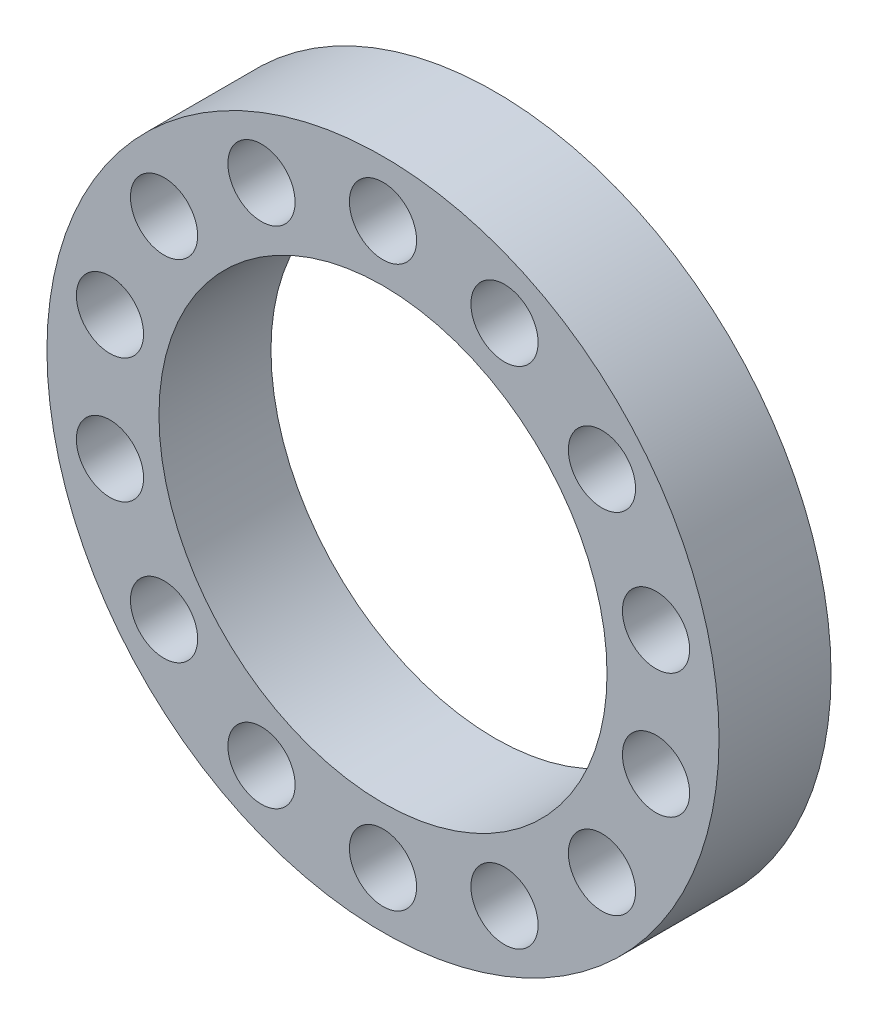
SolidWorks part; units mm, degrees
ref_plane "Plan de face" through (0, 0, 0) normal (0, 0, 1) x (1, 0, 0)
ref_plane "Plan de dessus" through (0, 0, 0) normal (0, 1, 0) x (1, 0, 0)
ref_plane "Plan de droite" through (0, 0, 0) normal (1, 0, 0) x (0, 0, -1)
sketch "Esquisse1" plane through (0, 0, 0) normal (0, 0, 1) x (1, 0, 0)
  circle A0 centre (0, 0) radius 100
  circle A1 centre (0, 0) radius 150
  dimension "D1" = 300
  dimension "D2" = 200
extrude "Boss.-Extru.1" add sketch "Esquisse1" along normal blind 50
sketch "Esquisse2" plane through (0, 0, 50) normal (0, 0, 1) x (1, 0, 0)
  line L0 (0, 100) -> (0, 150) construction
  circle A0 centre (0, 0) radius 100 construction
  circle A1 centre (0, 0) radius 150 construction
  circle A2 centre (0, 125) radius 15
  circle A3 centre (54.2355, 112.6211) radius 15
  circle A4 centre (97.7289, 77.9362) radius 15
  circle A5 centre (121.866, 27.8151) radius 15
  circle A6 centre (121.866, -27.8151) radius 15
  circle A7 centre (97.7289, -77.9362) radius 15
  circle A8 centre (54.2355, -112.6211) radius 15
  circle A9 centre (0, -125) radius 15
  circle A10 centre (-54.2355, -112.6211) radius 15
  circle A11 centre (-97.7289, -77.9362) radius 15
  circle A12 centre (-121.866, -27.8151) radius 15
  circle A13 centre (-121.866, 27.8151) radius 15
  circle A14 centre (-97.7289, 77.9362) radius 15
  circle A15 centre (-54.2355, 112.6211) radius 15
  point P37 (0, 0)
  dimension "D1" = 30
  dimension "D2" = 14
extrude "Enlèv. mat.-Extru.1" cut sketch "Esquisse2" against normal blind 40
sketch "Esquisse3" plane through (0, 0, 10) normal (0, 0, 1) x (1, 0, 0)
  circle A0 centre (0, 125) radius 6
  circle A1 centre (54.2355, 112.6211) radius 6
  circle A2 centre (97.7289, 77.9362) radius 6
  circle A3 centre (121.866, 27.8151) radius 6
  circle A4 centre (121.866, -27.8151) radius 6
  circle A5 centre (97.7289, -77.9362) radius 6
  circle A6 centre (54.2355, -112.6211) radius 6
  circle A7 centre (0, -125) radius 6
  circle A8 centre (-54.2355, -112.6211) radius 6
  circle A9 centre (-97.7289, -77.9362) radius 6
  circle A10 centre (-121.866, -27.8151) radius 6
  circle A11 centre (-121.866, 27.8151) radius 6
  circle A12 centre (-97.7289, 77.9362) radius 6
  circle A13 centre (-54.2355, 112.6211) radius 6
  point P31 (0, 0)
  dimension "D1" = 12
  dimension "D2" = 14
extrude "Enlèv. mat.-Extru.2" cut sketch "Esquisse3" against normal blind 10
